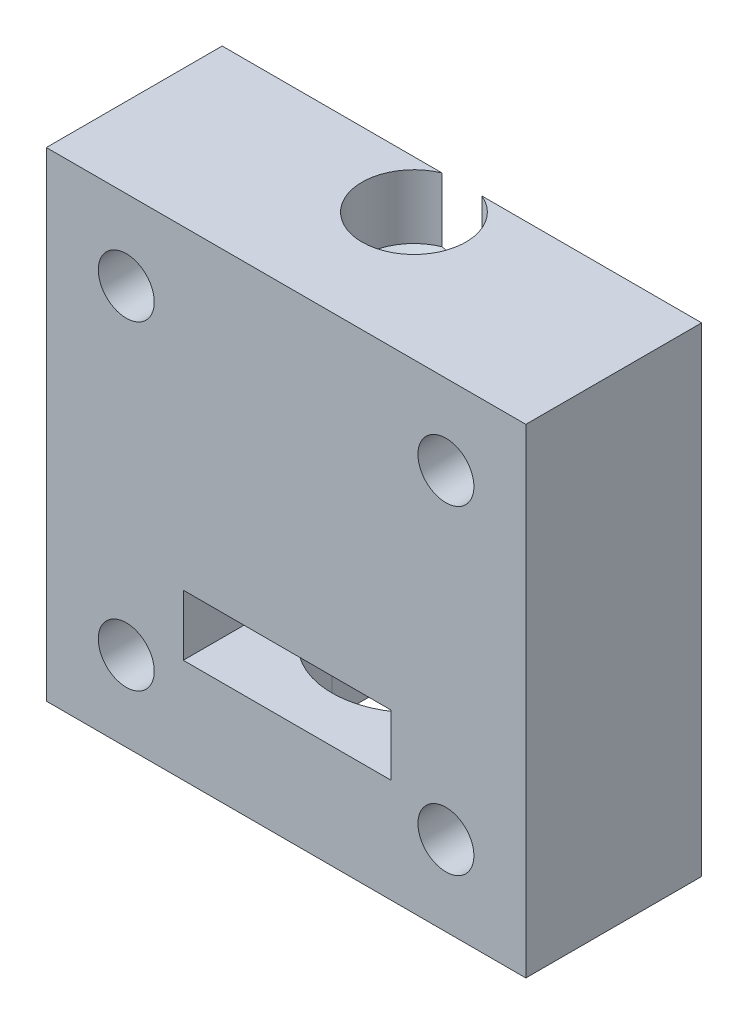
SolidWorks part; units mm, degrees
material "ABS"
ref_plane "Front Plane" through (0, 0, 0) normal (0, 0, 1) x (1, 0, 0)
ref_plane "Top Plane" through (0, 0, 0) normal (0, 1, 0) x (1, 0, 0)
ref_plane "Right Plane" through (0, 0, 0) normal (1, 0, 0) x (0, 0, -1)
ref_plane "Plane1" through (0, 0, 5) normal (0, 0, -1) x (-1, 0, 0)
sketch "Sketch1" plane through (0, 0, 5) normal (0, 0, -1) x (-1, 0, 0)
  line L0 (15, -15) -> (15, 15)
  line L1 (15, 15) -> (-15, 15)
  line L2 (-15, 15) -> (-15, -15)
  line L3 (-15, -15) -> (15, -15)
extrude "Boss-Extrude1" add sketch "Sketch1" against normal blind 11
ref_plane "Plane2" through (0, -4.95, 0) normal (0, 1, 0) x (1, 0, 0)
sketch "Sketch2" plane through (0, -4.95, 0) normal (0, 1, 0) x (1, 0, 0)
  line L0 (7.4327, -5) -> (-7.4327, -5)
  line L1 (-7.75, -6.6057) -> (-7.75, -8)
  arc A0 (-7.4327, -5) -> (-7.75, -6.6057) centre (0, -7.3028) ccw
  arc A1 (-7.75, -8) -> (7.4327, -5) centre (0, -7.3028) ccw
extrude "Cut-Extrude1" cut sketch "Sketch2" against normal blind 1.55
sketch "Sketch3" plane through (0, -6.5, 0) normal (0, 1, 0) x (-1, 0, 0)
  line L0 (-5.125, 5) -> (5.125, 5)
  line L1 (5.125, 5) -> (5.125, 8)
  line L2 (-5.125, 8) -> (-5.125, 5)
  arc A0 (5.125, 8) -> (-5.125, 8) centre (0, 8) ccw
extrude "Cut-Extrude2" cut sketch "Sketch3" against normal through all
sketch "Sketch4" plane through (0, 0, 5) normal (0, 0, -1) x (-1, 0, 0)
  line L0 (0.5175, 0.6395) -> (0.5175, 2.9172)
  line L1 (-0.8463, 3.1605) -> (-0.8463, 0.6395)
  line L2 (-0.8463, 0.6395) -> (-1.9099, 0.6395)
  line L3 (-1.9099, 0.6395) -> (-1.9099, 4.5388)
  line L4 (-1.9099, 4.5388) -> (-1.0974, 4.5388)
  line L5 (-1.0974, 4.5388) -> (-1.0974, 3.6947)
  line L6 (4.0117, 3.9317) -> (4.0117, 0.6395)
  line L7 (4.0117, 0.6395) -> (2.9448, 0.6395)
  line L8 (2.9448, 0.6395) -> (2.9448, 2.9172)
  line L9 (1.581, 3.2029) -> (1.581, 0.6395)
  line L10 (1.581, 0.6395) -> (0.5175, 0.6395)
  arc A0 (1.9806, 4.4618) -> (2.6692, 4.6114) centre (2.6446, 3.0642) cw
  spline S0 degree 2 poles (0.5175, 2.9172) (0.5175, 3.3391) (0.3057, 3.6555) (0.2351, 3.761) knots 0 0 0 1 1.5 1.5 1.5
  spline S1 degree 2 poles (0.2351, 3.761) (0.0833, 3.761) (-0.4769, 3.761) (-0.7539, 3.3106) (-0.8463, 3.1605) knots -0.371585 -0.371585 -0.371585 0 1 1.5 1.5 1.5
  spline S2 degree 2 poles (-1.0974, 3.6947) (-0.9964, 3.8673) (-0.738, 4.3089) (-0.2936, 4.5357) (-0.1454, 4.6114) knots -0.641844 -0.641844 -0.641844 0 1 1.5 1.5 1.5
  spline S3 degree 2 poles (-0.1454, 4.6114) (0.0465, 4.6114) (1.1134, 4.6114) (1.4475, 3.9982) (1.4703, 3.9565) knots -0.219388 -0.219388 -0.219388 0 1 1.07306 1.07306 1.07306
  spline S4 degree 2 poles (1.4703, 3.9565) (1.4944, 3.9982) (1.6759, 4.3123) (1.9806, 4.4618) knots -0.153307 -0.153307 -0.153307 0 1 1 1
  spline S5 degree 2 poles (2.6692, 4.6114) (3.3321, 4.6114) (3.8418, 4.1016) (4.0117, 3.9317) knots 0 0 0 1 1.5 1.5 1.5
  spline S6 degree 2 poles (2.9448, 2.9172) (2.9448, 3.3391) (2.733, 3.6555) (2.6625, 3.761) knots 0 0 0 1 1.5 1.5 1.5
  spline S7 degree 2 poles (2.6625, 3.761) (2.5107, 3.761) (1.9683, 3.761) (1.6779, 3.3424) (1.581, 3.2029) knots -0.388571 -0.388571 -0.388571 0 1 1.5 1.5 1.5
sketch "Sketch5" plane through (0, 0, 5) normal (0, 0, -1) x (-1, 0, 0)
  line L0 (-7.7589, 5.7385) -> (-4.9934, 5.7385)
  line L1 (-4.9934, 5.7385) -> (-4.9934, 4.8245)
  line L2 (-4.9934, 4.8245) -> (-6.8136, 4.8245)
  line L3 (-6.8136, 4.8245) -> (-6.8136, 3.8424)
  line L4 (-6.8136, 3.8424) -> (-6.7857, 3.848)
  line L5 (-8.0513, 0.8448) -> (-8.0513, 1.7767)
  line L6 (-7.5212, 2.9094) -> (-7.7589, 3.0372)
  line L7 (-7.7589, 3.0372) -> (-7.7589, 5.7385)
  arc A0 (-6.7857, 3.848) -> (-6.259, 3.8971) centre (-6.2996, 1.483) cw
  arc A1 (-6.9353, 3.0255) -> (-7.5212, 2.9094) centre (-6.3552, -1.4396) ccw
  spline S0 degree 2 poles (-6.259, 3.8971) (-5.5202, 3.8971) (-4.8631, 3.2744) (-4.6441, 3.0668) knots 0 0 0 1 1.5 1.5 1.5
  spline S1 degree 2 poles (-4.6441, 3.0668) (-4.6441, 2.7058) (-4.6441, 1.491) (-5.4342, 0.7996) (-5.6976, 0.5691) knots -0.422876 -0.422876 -0.422876 0 1 1.5 1.5 1.5
  spline S2 degree 2 poles (-5.6976, 0.5691) (-6.1876, 0.5691) (-7.529, 0.5691) (-8.0513, 0.8448) knots -0.57536 -0.57536 -0.57536 0 1 1 1
  spline S3 degree 2 poles (-8.0513, 1.7767) (-7.7768, 1.6305) (-7.2268, 1.4915) (-7.0435, 1.4452) knots 0 0 0 1 1.5 1.5 1.5
  spline S4 degree 2 poles (-7.0435, 1.4452) (-6.88, 1.4452) (-5.7289, 1.4452) (-5.7289, 2.2543) knots -0.165537 -0.165537 -0.165537 0 1 1 1
  spline S5 degree 2 poles (-5.7289, 2.2543) (-5.7289, 3.0255) (-6.8432, 3.0255) (-6.9353, 3.0255) knots 0 0 0 1 1.090066 1.090066 1.090066
sketch "Sketch6" plane through (0, 0, 5) normal (0, 0, -1) x (-1, 0, 0)
  line L0 (5.1869, 5.7385) -> (6.2683, 5.7385)
  line L1 (6.2683, 5.7385) -> (6.2683, 1.5323)
  line L2 (6.2683, 1.5323) -> (8.3363, 1.5323)
  line L3 (8.3363, 1.5323) -> (8.3363, 0.6395)
  line L4 (8.3363, 0.6395) -> (5.1869, 0.6395)
  line L5 (5.1869, 0.6395) -> (5.1869, 5.7385)
sketch "Sketch7" plane through (0, 0, 5) normal (0, 0, -1) x (-1, 0, 0)
  line L0 (2.775, -2.45) -> (2.775, -0.65)
  line L1 (2.775, -0.65) -> (-2.775, -0.65)
  line L2 (-2.775, -0.65) -> (-2.775, -2.45)
  line L3 (-2.775, -2.45) -> (2.775, -2.45)
extrude "Cut-Extrude3" cut sketch "Sketch7" against normal blind 5.55
hole_wizard "CBORE for M3 Hex Head Machine Screw1" positions "Sketch9" profile "Sketch8" counterbore size "M3" standard "ANSI Metric"
sketch "Sketch9" plane through (0, 0, 5) normal (0, 0, -1) x (-1, 0, 0)
  point P0 (-10, 10)
  point P1 (-10, -10)
  point P2 (10, -10)
  point P3 (10, 10)
sketch "Sketch8" plane through (10, 10, 5) normal (1, 0, 0) x (0, 1, 0)
  line L0 (0, 0) -> (0, 11)
  line L1 (0, 11) -> (1.75, 11)
  line L3 (1.75, 11) -> (1.75, 4)
  line L4 (1.75, 4) -> (3.25, 4)
  line L5 (3.25, 4) -> (3.25, 0)
  line L7 (3.25, 0) -> (0, 0)
  line L11 (0, -6.35) -> (0, 107.95) construction
  dimension "Thru Hole Dia." = 3.5
  dimension "Thru Hole Depth" = 11
  dimension "C'Bore Dia." = 6.5
  dimension "C'Bore Depth" = 4
hole_wizard "Ø3.4 (3.4) Diameter Hole1" positions "Sketch11" profile "Sketch10" hole size "Ø3.4" standard "ANSI Metric"
sketch "Sketch11" plane through (0, -2.45, 0) normal (0, 1, 0) x (1, 0, 0)
  point P0 (0, -8)
sketch "Sketch10" plane through (0, -2.45, 8) normal (1, 0, 0) x (0, 0, 1)
  line L0 (0, 0) -> (0, 12.55)
  line L1 (0, 12.55) -> (1.7, 12.55)
  line L2 (1.7, 12.55) -> (1.7, 0)
  line L5 (1.7, 0) -> (0, 0)
  line L11 (0, -6.35) -> (0, 107.95) construction
  dimension "Thru Hole Dia." = 3.4
  dimension "Thru Hole Depth" = 12.55
hole_wizard "CSK for M3 Flat Head Machine Screw1" positions "Sketch13" profile "Sketch12" countersink size "M3" standard "ANSI Metric"
sketch "Sketch13" plane through (0, 15, 0) normal (0, 1, 0) x (1, 0, 0)
  point P0 (0, -8)
sketch "Sketch12" plane through (0, 15, 8) normal (1, 0, 0) x (0, 0, 1)
  line L0 (0, 0) -> (0, 30)
  line L1 (0, 30) -> (1.7, 30)
  line L2 (1.7, 30) -> (1.7, 4.9313)
  line L3 (1.7, 4.9313) -> (3.25, 4)
  line L4 (3.25, 4) -> (3.25, 0)
  line L6 (3.25, 0) -> (0, 0)
  line L7 (-1.7, 4.9313) -> (-3.25, 4) construction
  line L11 (0, -6.35) -> (0, 107.95) construction
  dimension "Thru Hole Dia." = 3.4
  dimension "Thru Hole Depth" = 30
  dimension "C'Sink Dia." = 6.5
  dimension "C'Sink Angle" = 118
  dimension "Head Clearance" = 4
sketch "Sketch14" plane through (0, -6.5, 0) normal (0, 1, 0) x (-1, 0, 0)
  line L0 (6.4316, -10) -> (-6.5684, -10)
  line L1 (6.4316, -10) -> (6.4316, 20)
  line L2 (6.4316, 20) -> (-6.5684, 20)
  line L3 (-6.5684, -10) -> (-6.5684, 20)
extrude "Cut-Extrude4" cut sketch "Sketch14" along normal blind 1.8 and the other way blind 2
